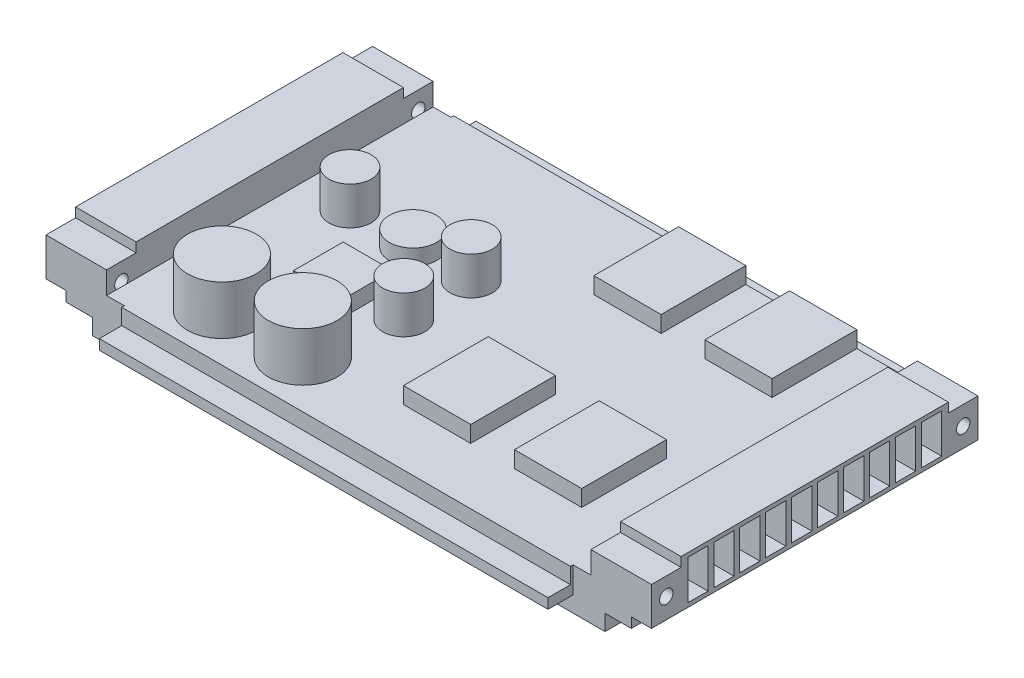
SolidWorks part; units mm, degrees
ref_plane "前视基准面" through (0, 0, 0) normal (0, 0, 1) x (1, 0, 0)
ref_plane "上视基准面" through (0, 0, 0) normal (0, 1, 0) x (1, 0, 0)
ref_plane "右视基准面" through (0, 0, 0) normal (1, 0, 0) x (0, 0, -1)
sketch "草图1" plane through (0, 0, 0) normal (0, 1, 0) x (1, 0, 0)
  line L0 (-5.9932, 46.67) -> (-5.9932, -1.87)
  line L1 (5.6568, 50.4) -> (72.3568, 50.4)
  line L2 (5.6568, -5.6) -> (72.3568, -5.6)
  line L3 (84.0068, -1.87) -> (84.0068, 46.67)
  line L4 (-5.9932, 22.4) -> (84.0068, 22.4) construction
  line L5 (5.6568, 46.67) -> (5.6568, 50.4)
  line L6 (39.0068, 50.4) -> (39.0068, -5.6) construction
  line L7 (84.0068, 46.67) -> (72.3568, 46.67)
  line L8 (-5.9932, 46.67) -> (5.6568, 46.67)
  line L9 (72.3568, 46.67) -> (72.3568, 50.4)
  line L10 (5.6568, -5.6) -> (5.6568, -1.87)
  line L11 (5.6568, -1.87) -> (-5.9932, -1.87)
  line L12 (72.3568, -5.6) -> (72.3568, -1.87)
  line L13 (72.3568, -1.87) -> (84.0068, -1.87)
  dimension "D1" = 48.54
  dimension "D2" = 66.7
  dimension "D3" = 11.65
  dimension "D4" = 3.73
  dimension "D5" = 11.65
  dimension "D6" = 3.73
extrude "凸台-拉伸1" add sketch "草图1" along normal blind 1.5
sketch "草图2" plane through (0, 1.5, 0) normal (0, 1, 0) x (1, 0, 0)
  line L0 (-5.9932, 46.67) -> (3.0068, 46.67)
  line L1 (5.6568, 46.67) -> (-5.9932, 46.67) construction
  line L2 (3.0068, 46.67) -> (3.0068, -1.87)
  line L3 (-5.9932, -1.87) -> (5.6568, -1.87) construction
  line L4 (3.0068, -1.87) -> (-5.9932, -1.87)
  line L5 (-5.9932, -1.87) -> (-5.9932, 46.67)
  line L6 (84.0068, 46.67) -> (75.0105, 46.67)
  line L7 (84.0068, 46.67) -> (72.3568, 46.67) construction
  line L8 (75.0105, 46.67) -> (75.0105, -1.87)
  line L9 (72.3568, -1.87) -> (84.0068, -1.87) construction
  line L10 (75.0105, -1.87) -> (84.0068, -1.87)
  line L11 (84.0068, -1.87) -> (84.0068, 46.67) construction
  line L12 (84.0068, -1.87) -> (84.0068, 46.67)
  dimension "D1" = 9
extrude "凸台-拉伸2" add sketch "草图2" along normal blind 7.06
sketch "草图3" plane through (0, 1.5, 0) normal (0, 1, 0) x (1, 0, 0)
  line L0 (3.0068, -1.87) -> (3.0068, 46.67) construction
  line L2 (5.6568, -5.6) -> (72.3568, -5.6) construction
  line L4 (8.4068, -0.34) -> (8.4068, 9.88)
  line L5 (8.4068, 9.88) -> (18.6268, 9.88)
  line L6 (8.4068, -0.34) -> (18.6268, -0.34)
  line L7 (18.6268, -0.34) -> (18.6268, 9.88)
  line L9 (20.4268, -0.34) -> (20.4268, 9.88)
  line L10 (20.4268, 9.88) -> (30.6468, 9.88)
  line L11 (30.6468, 9.88) -> (30.6468, -0.34)
  line L12 (30.6468, -0.34) -> (20.4268, -0.34)
  dimension "D1" = 5.4
  dimension "D2" = 5.26
  dimension "D3" = 10.22
  dimension "D4" = 10.22
  dimension "D5" = 5.26
  dimension "D6" = 10.22
  dimension "D7" = 10.22
  dimension "D8" = 1.8
extrude "凸台-拉伸3" add sketch "草图3" along normal blind 2.14
sketch "草图4" plane through (0, 3.64, 0) normal (0, 1, 0) x (1, 0, 0)
  circle A2 centre (13.5168, 4.77) radius 5.11
  circle A3 centre (25.5368, 4.77) radius 5.11
extrude "凸台-拉伸4" add sketch "草图4" along normal blind 7.5
sketch "草图5" plane through (0, 1.5, 0) normal (0, 1, 0) x (1, 0, 0)
  line L0 (7.0448, 30.28) -> (13.3248, 30.28)
  line L1 (13.3248, 30.28) -> (13.3248, 24)
  line L2 (25.5368, -0.34) -> (30.6468, -0.34) construction
  line L3 (3.0068, -1.87) -> (3.0068, 46.67) construction
  line L4 (7.0448, 30.28) -> (7.0448, 24)
  line L5 (7.0448, 24) -> (13.3248, 24)
  line L6 (8.4068, -0.34) -> (13.5168, -0.34) construction
  line L7 (23.04, 23.64) -> (16.04, 23.64)
  line L8 (25.06, 30.28) -> (25.06, 24)
  line L9 (25.06, 24) -> (31.3431, 24)
  line L10 (31.3431, 24) -> (31.3431, 30.28)
  line L11 (31.3431, 30.28) -> (25.06, 30.28)
  line L12 (31.3431, 20.2582) -> (25.06, 20.2582)
  line L13 (25.06, 20.2582) -> (25.06, 13.9817)
  line L14 (25.06, 13.9817) -> (31.3431, 13.9817)
  line L15 (31.3431, 13.9817) -> (31.3431, 20.2582)
  line L16 (16.04, 30.64) -> (23.04, 30.64)
  line L17 (23.04, 30.64) -> (23.04, 23.64)
  line L18 (16.04, 23.64) -> (16.04, 30.64)
  point P8 (10.9618, -0.34)
  dimension "D1" = 6.28
  dimension "D2" = 6.28
  dimension "D3" = 4.038
  dimension "D4" = 30.62
  dimension "D5" = 11.7352
  dimension "D6" = 6.2831
  dimension "D7" = 6.28
  dimension "D8" = 3.7418
  dimension "D9" = 6.2766
  dimension "D10" = 6.2831
  dimension "D11" = 7
  dimension "D12" = 2.02
  dimension "D13" = 0.36
  dimension "D14" = 7
  dimension "D15" = 30.62
extrude "凸台-拉伸5" add sketch "草图5" along normal blind 2.14
sketch "草图6" plane through (0, 3.64, 0) normal (0, 1, 0) x (1, 0, 0)
  line L0 (13.3248, 30.28) -> (7.0448, 30.28) construction
  line L1 (23.04, 30.64) -> (16.04, 30.64) construction
  line L2 (31.3431, 30.28) -> (25.06, 30.28) construction
  line L3 (31.3431, 20.2582) -> (25.06, 20.2582) construction
  circle A0 centre (10.1848, 27.14) radius 3.14
  circle A1 centre (19.54, 27.14) radius 3.5
  circle A2 centre (28.2016, 27.14) radius 3.1416
  circle A3 centre (28.2016, 17.1182) radius 3.1416
  dimension "D4" = 3.14
  dimension "D1" = 3.14
  dimension "D2" = 3.5
  dimension "D3" = 3.14
extrude "凸台-拉伸6" add sketch "草图6" along normal blind 5.86
sketch "草图7" plane through (0, 9.5, 0) normal (0, 1, 0) x (1, 0, 0)
  circle A0 centre (19.54, 27.14) radius 3.5
extrude "切除-拉伸1" cut sketch "草图7" against normal blind 3.3
sketch "草图8" plane through (0, 1.5, 0) normal (0, 1, 0) x (1, 0, 0)
  line L0 (16.04, 20.2582) -> (16.04, 12.8982)
  line L1 (16.04, 20.2582) -> (23.4, 20.2582)
  line L2 (16.04, 12.8982) -> (23.4, 12.8982)
  line L3 (23.4, 12.8982) -> (23.4, 20.2582)
  line L4 (28.1021, 20.2582) -> (25.06, 20.2582) construction
  dimension "D1" = 7.36
  dimension "D2" = 7.36
  dimension "D3" = 0
extrude "凸台-拉伸7" add sketch "草图8" along normal blind 4.7
sketch "草图10" plane through (0, 1.5, 0) normal (0, 1, 0) x (1, 0, 0)
  line L0 (72.3568, 50.4) -> (5.6568, 50.4) construction
  line L2 (75.0105, 46.67) -> (75.0105, -1.87) construction
  line L3 (65.6105, 47.06) -> (65.6105, 34.46)
  line L4 (65.6105, 34.46) -> (55.6105, 34.46)
  line L5 (55.6105, 34.46) -> (55.6105, 47.06)
  line L6 (55.6105, 47.06) -> (65.6105, 47.06)
  line L7 (75.0105, 46.67) -> (75.0105, -1.87) construction
  line L8 (55.6105, 18.76) -> (65.6105, 18.76)
  line L9 (65.6105, 18.76) -> (65.6105, 6.1582)
  line L10 (65.6105, 6.1582) -> (55.6105, 6.1582)
  line L11 (55.6105, 6.1582) -> (55.6105, 18.76)
  line L13 (49.1105, 6.1582) -> (49.1105, 18.76)
  line L14 (49.1105, 18.76) -> (39.1105, 18.76)
  line L15 (39.1105, 18.76) -> (39.1105, 6.1582)
  line L16 (39.1105, 6.1582) -> (49.1105, 6.1582)
  line L17 (49.1105, 34.46) -> (39.1105, 34.46)
  line L18 (39.1105, 34.46) -> (39.1105, 47.06)
  line L19 (39.1105, 47.06) -> (49.1105, 47.06)
  line L20 (49.1105, 47.06) -> (49.1105, 34.46)
  dimension "D1" = 3.34
  dimension "D2" = 9.4
  dimension "D3" = 15.7
  dimension "D4" = 12.6
  dimension "D5" = 10
  dimension "D6" = 12.6018
  dimension "D7" = 10
  dimension "D8" = 9.4
  dimension "D9" = 6.5
  dimension "D10" = 10
extrude "凸台-拉伸8" add sketch "草图10" along normal blind 4.8
sketch "草图11" plane through (0, 1.5, 0) normal (0, 1, 0) x (1, 0, 0)
  line L0 (65.6105, 47.06) -> (72.3568, 47.06)
  line L1 (72.3568, 46.67) -> (72.3568, 50.4) construction
  line L2 (72.3568, 47.06) -> (72.3568, 46.67)
  line L3 (72.3568, 46.67) -> (75.0105, 46.67)
  line L4 (75.0105, 46.67) -> (75.0105, -1.87)
  line L5 (75.0105, -1.87) -> (72.3568, -1.87)
  line L6 (75.0105, 22.4) -> (66.5835, 22.4) construction
  line L7 (72.3568, -2.26) -> (72.3568, -1.87)
  line L8 (65.6105, -2.26) -> (72.3568, -2.26)
  line L9 (65.6105, -2.26) -> (5.6568, -2.26)
  line L10 (5.6568, -1.87) -> (5.6568, -5.6) construction
  line L11 (5.6568, -2.26) -> (5.6568, -1.87)
  line L12 (5.6568, -1.87) -> (3.0068, -1.87)
  line L13 (3.0068, -1.87) -> (3.0068, 46.67)
  line L14 (3.0068, 46.67) -> (5.6568, 46.67)
  line L15 (5.6568, 46.67) -> (5.6568, 47.06)
  line L16 (5.6568, 50.4) -> (5.6568, 46.67) construction
  line L17 (5.6568, 47.06) -> (65.6105, 47.06)
extrude "凸台-拉伸9" add sketch "草图11" along normal blind 2.36
sketch "草图12" plane through (0, 0, 0) normal (0, -1, 0) x (1, 0, 0)
  line L0 (0.9068, -46.67) -> (0.9068, 1.87)
  line L3 (5.6568, -46.67) -> (-5.9932, -46.67) construction
  line L4 (77.1068, -46.67) -> (0.9068, -46.67)
  line L5 (84.0068, -46.67) -> (72.3568, -46.67) construction
  line L6 (77.1068, -46.67) -> (77.1068, 1.87)
  line L8 (72.3568, 1.87) -> (84.0068, 1.87) construction
  line L9 (77.1068, 1.87) -> (0.9068, 1.87)
  line L10 (-5.9932, 1.87) -> (5.6568, 1.87) construction
extrude "凸台-拉伸10" add sketch "草图12" along normal blind 2.36
sketch "草图13" plane through (0, 0, 0) normal (0, -1, 0) x (1, 0, 0)
  line L0 (-5.9932, 1.87) -> (-2.9932, 1.87)
  line L1 (-5.9932, 1.87) -> (0.9068, 1.87) construction
  line L2 (-2.9932, 1.87) -> (-2.9932, -46.67)
  line L3 (0.9068, -46.67) -> (-5.9932, -46.67) construction
  line L4 (-2.9932, -46.67) -> (-5.9932, -46.67)
  line L5 (-5.9932, -46.67) -> (-5.9932, 1.87)
  line L6 (84.0068, 1.87) -> (81.0068, 1.87)
  line L7 (77.1068, 1.87) -> (84.0068, 1.87) construction
  line L8 (81.0068, 1.87) -> (81.0068, -46.67)
  line L9 (84.0068, -46.67) -> (77.1068, -46.67) construction
  line L10 (81.0068, -46.67) -> (84.0068, -46.67)
  line L11 (84.0068, -46.67) -> (84.0068, 1.87)
  dimension "D1" = 3
  dimension "D2" = 3
extrude "切除-拉伸2" cut sketch "草图13" against normal up to surface (1.5 mm away)
sketch "草图14" plane through (-5.9932, 0, 0) normal (-1, 0, 0) x (0, 0, 1)
  line L0 (-46.67, 8.56) -> (-46.67, 1.5) construction
  line L1 (-37.41, 7.96) -> (-37.41, 2.0799)
  line L2 (-46.67, 8.56) -> (1.87, 8.56) construction
  line L3 (-37.41, 2.0799) -> (-34.4123, 2.0799)
  line L4 (-34.4123, 2.0799) -> (-34.4123, 7.96)
  line L5 (-41.27, 7.96) -> (-41.27, 2.0799)
  line L6 (-41.27, 2.0799) -> (-38.2723, 2.0799)
  line L7 (-38.2723, 2.0799) -> (-38.2723, 7.96)
  line L8 (-38.2723, 7.96) -> (-41.27, 7.96)
  line L9 (-34.4123, 7.96) -> (-37.41, 7.96)
  line L10 (-33.55, 7.96) -> (-33.55, 2.0799)
  line L11 (-33.55, 2.0799) -> (-30.5523, 2.0799)
  line L12 (-30.5523, 2.0799) -> (-30.5523, 7.96)
  line L13 (-30.5523, 7.96) -> (-33.55, 7.96)
  line L14 (-29.69, 7.96) -> (-29.69, 2.0799)
  line L15 (-29.69, 2.0799) -> (-26.6923, 2.0799)
  line L16 (-26.6923, 2.0799) -> (-26.6923, 7.96)
  line L17 (-26.6923, 7.96) -> (-29.69, 7.96)
  line L18 (-25.83, 7.96) -> (-25.83, 2.0799)
  line L19 (-25.83, 2.0799) -> (-22.8323, 2.0799)
  line L20 (-22.8323, 2.0799) -> (-22.8323, 7.96)
  line L21 (-22.8323, 7.96) -> (-25.83, 7.96)
  line L22 (-21.97, 7.96) -> (-21.97, 2.0799)
  line L23 (-21.97, 2.0799) -> (-18.9723, 2.0799)
  line L24 (-18.9723, 2.0799) -> (-18.9723, 7.96)
  line L25 (-18.9723, 7.96) -> (-21.97, 7.96)
  line L26 (-18.11, 7.96) -> (-18.11, 2.0799)
  line L27 (-18.11, 2.0799) -> (-15.1123, 2.0799)
  line L28 (-15.1123, 2.0799) -> (-15.1123, 7.96)
  line L29 (-15.1123, 7.96) -> (-18.11, 7.96)
  line L30 (-14.25, 7.96) -> (-14.25, 2.0799)
  line L31 (-14.25, 2.0799) -> (-11.2523, 2.0799)
  line L32 (-11.2523, 2.0799) -> (-11.2523, 7.96)
  line L33 (-11.2523, 7.96) -> (-14.25, 7.96)
  line L34 (-10.39, 7.96) -> (-10.39, 2.0799)
  line L35 (-10.39, 2.0799) -> (-7.3923, 2.0799)
  line L36 (-7.3923, 2.0799) -> (-7.3923, 7.96)
  line L37 (-7.3923, 7.96) -> (-10.39, 7.96)
  line L38 (-6.53, 7.96) -> (-6.53, 2.0799)
  line L39 (-6.53, 2.0799) -> (-3.5323, 2.0799)
  line L40 (-3.5323, 2.0799) -> (-3.5323, 7.96)
  line L41 (-3.5323, 7.96) -> (-6.53, 7.96)
  line L42 (1.87, 8.56) -> (1.87, 1.5) construction
  dimension "D1" = 5.4
  dimension "D2" = 5.8801
  dimension "D3" = 2.9977
  dimension "D4" = 0.6
  dimension "D6" = 5.4023
  dimension "D5" = 10
extrude "切除-拉伸3" cut sketch "草图14" against normal blind 5
sketch "草图15" plane through (84.0068, 0, 0) normal (1, 0, 0) x (0, 0, -1)
  line L0 (-1.87, 1.5) -> (46.67, 1.5) construction
  line L2 (-1.87, 8.56) -> (-1.87, 1.5) construction
  line L4 (-1.87, 8.56) -> (46.67, 8.56) construction
  line L6 (3.53, 2.1031) -> (3.53, 7.96)
  line L7 (3.53, 7.96) -> (6.53, 7.96)
  line L8 (6.53, 7.96) -> (6.53, 2.1031)
  line L9 (6.53, 2.1031) -> (3.53, 2.1031)
  line L10 (7.39, 2.1031) -> (7.39, 7.96)
  line L11 (7.39, 7.96) -> (10.39, 7.96)
  line L12 (10.39, 7.96) -> (10.39, 2.1031)
  line L13 (10.39, 2.1031) -> (7.39, 2.1031)
  line L14 (11.25, 2.1031) -> (11.25, 7.96)
  line L15 (11.25, 7.96) -> (14.25, 7.96)
  line L16 (14.25, 7.96) -> (14.25, 2.1031)
  line L17 (14.25, 2.1031) -> (11.25, 2.1031)
  line L18 (15.11, 2.1031) -> (15.11, 7.96)
  line L19 (15.11, 7.96) -> (18.11, 7.96)
  line L20 (18.11, 7.96) -> (18.11, 2.1031)
  line L21 (18.11, 2.1031) -> (15.11, 2.1031)
  line L22 (18.97, 2.1031) -> (18.97, 7.96)
  line L23 (18.97, 7.96) -> (21.97, 7.96)
  line L24 (21.97, 7.96) -> (21.97, 2.1031)
  line L25 (21.97, 2.1031) -> (18.97, 2.1031)
  line L26 (22.83, 2.1031) -> (22.83, 7.96)
  line L27 (22.83, 7.96) -> (25.83, 7.96)
  line L28 (25.83, 7.96) -> (25.83, 2.1031)
  line L29 (25.83, 2.1031) -> (22.83, 2.1031)
  line L30 (26.69, 2.1031) -> (26.69, 7.96)
  line L31 (26.69, 7.96) -> (29.69, 7.96)
  line L32 (29.69, 7.96) -> (29.69, 2.1031)
  line L33 (29.69, 2.1031) -> (26.69, 2.1031)
  line L34 (30.55, 2.1031) -> (30.55, 7.96)
  line L35 (30.55, 7.96) -> (33.55, 7.96)
  line L36 (33.55, 7.96) -> (33.55, 2.1031)
  line L37 (33.55, 2.1031) -> (30.55, 2.1031)
  line L38 (34.41, 2.1031) -> (34.41, 7.96)
  line L39 (34.41, 7.96) -> (37.41, 7.96)
  line L40 (37.41, 7.96) -> (37.41, 2.1031)
  line L41 (37.41, 2.1031) -> (34.41, 2.1031)
  line L42 (38.27, 2.1031) -> (38.27, 7.96)
  line L43 (38.27, 7.96) -> (41.27, 7.96)
  line L44 (41.27, 7.96) -> (41.27, 2.1031)
  line L45 (41.27, 2.1031) -> (38.27, 2.1031)
  line L46 (46.67, 8.56) -> (46.67, 1.5) construction
  dimension "D1" = 0.6031
  dimension "D2" = 5.4
  dimension "D3" = 3
  dimension "D4" = 0.6
  dimension "D6" = 5.4
  dimension "D5" = 10
extrude "切除-拉伸4" cut sketch "草图15" against normal blind 5
sketch "草图16" plane through (0, 8.56, 0) normal (0, 1, 0) x (1, 0, 0)
  line L0 (3.0068, 46.67) -> (3.0068, 42.27)
  line L1 (3.0068, 46.67) -> (3.0068, -1.87) construction
  line L2 (3.0068, 42.27) -> (-5.9932, 42.27)
  line L3 (-5.9932, 46.67) -> (-5.9932, -1.87) construction
  line L4 (-5.9932, 42.27) -> (-5.9932, 46.67)
  line L5 (-5.9932, 46.67) -> (3.0068, 46.67)
  line L6 (3.0068, -1.87) -> (3.0068, 2.53)
  line L7 (3.0068, 2.53) -> (-5.9932, 2.53)
  line L8 (-5.9932, 2.53) -> (-5.9932, -1.87)
  line L9 (-5.9932, -1.87) -> (3.0068, -1.87)
  line L10 (75.0105, -1.87) -> (75.0105, 2.53)
  line L11 (75.0105, 46.67) -> (75.0105, -1.87) construction
  line L12 (75.0105, 2.53) -> (84.0068, 2.53)
  line L13 (84.0068, -1.87) -> (84.0068, 46.67) construction
  line L14 (84.0068, 2.53) -> (84.0068, -1.87)
  line L15 (75.0105, -1.87) -> (84.0068, -1.87) construction
  line L16 (84.0068, -1.87) -> (75.0105, -1.87)
  line L17 (75.0105, 46.67) -> (75.0105, 42.27)
  line L18 (75.0105, 42.27) -> (84.0068, 42.27)
  line L19 (84.0068, 42.27) -> (84.0068, 46.67)
  line L20 (84.0068, 46.67) -> (75.0105, 46.67)
  dimension "D1" = 4.4
  dimension "D2" = 4.4
extrude "切除-拉伸5" cut sketch "草图16" against normal blind 1.4
sketch "草图17" plane through (-5.9932, 0, 0) normal (-1, 0, 0) x (0, 0, 1)
  circle A0 centre (-44.47, 4.51) radius 1
  circle A1 centre (-0.33, 4.51) radius 1
extrude "切除-拉伸6" cut sketch "草图17" against normal up to surface (9 mm away)
sketch "草图18" plane through (84.0068, 0, 0) normal (1, 0, 0) x (0, 0, -1)
  circle A0 centre (0.33, 4.51) radius 1
  circle A1 centre (44.47, 4.3752) radius 1
extrude "切除-拉伸7" cut sketch "草图18" against normal up to surface (8.9963 mm away)
